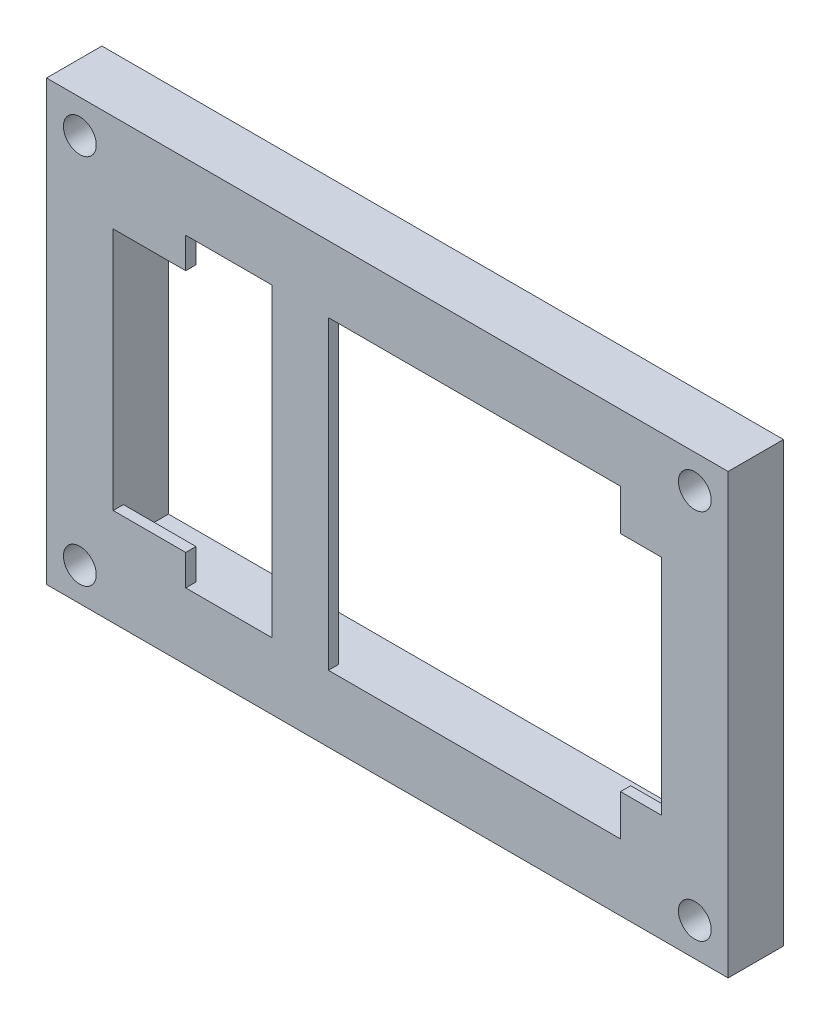
SolidWorks part; units mm, degrees
ref_plane "Front" through (0, 0, 0) normal (0, 0, 1) x (1, 0, 0)
ref_plane "Top" through (0, 0, 0) normal (0, 1, 0) x (1, 0, 0)
ref_plane "Right" through (0, 0, 0) normal (1, 0, 0) x (0, 0, -1)
sketch "Szkic1" plane through (0, 0, 0) normal (0, 0, 1) x (1, 0, 0)
  line L1 (-102.3488, 61.0183) -> (-35.8488, 61.0183)
  line L2 (-102.3488, 61.0183) -> (-102.3488, 18.2183)
  line L3 (-102.3488, 18.2183) -> (-35.8488, 18.2183)
  line L4 (-35.8488, 61.0183) -> (-35.8488, 18.2183)
  dimension "D1" = 66.5
  dimension "D2" = 42.8
extrude "Dodanie-wyciągnięcie1" add sketch "Szkic1" along normal blind 5.4
sketch "Szkic2" plane through (0, 0, 5.4) normal (0, 0, 1) x (1, 0, 0)
  line L0 (-35.8488, 18.2183) -> (-35.8488, 61.0183) construction
  line L1 (-42.3488, 54.5183) -> (-95.8488, 54.5183)
  line L2 (-42.3488, 54.5183) -> (-42.3488, 24.7183)
  line L3 (-42.3488, 24.7183) -> (-95.8488, 24.7183)
  line L4 (-95.8488, 54.5183) -> (-95.8488, 24.7183)
  line L5 (-35.8488, 61.0183) -> (-102.3488, 61.0183) construction
  line L6 (-102.3488, 18.2183) -> (-35.8488, 18.2183) construction
  line L7 (-102.3488, 61.0183) -> (-102.3488, 18.2183) construction
  dimension "D1" = 6.5
  dimension "D2" = 6.5
  dimension "D3" = 6.5
  dimension "D4" = 6.5
extrude "Wytnij-wyciągnięcie1" cut sketch "Szkic2" against normal through all
sketch "Szkic3" plane through (0, 0, 5.4) normal (0, 0, 1) x (1, 0, 0)
  line L0 (-42.3488, 54.5183) -> (-35.8488, 61.0183) construction
  line L1 (-42.3488, 24.7183) -> (-35.8488, 18.2183) construction
  line L2 (-95.8488, 24.7183) -> (-102.3488, 18.2183) construction
  line L3 (-95.8488, 54.5183) -> (-102.3488, 61.0183) construction
  circle A1 centre (-99.0988, 57.7683) radius 1.6
  circle A2 centre (-39.0988, 57.7683) radius 1.6
  circle A3 centre (-39.0988, 21.4683) radius 1.6
  circle A4 centre (-99.0988, 21.4683) radius 1.6
extrude "Wytnij-wyciągnięcie2" cut sketch "Szkic3" against normal blind 10
sketch "Szkic5" plane through (0, 54.5183, 0) normal (0, -1, 0) x (1, 0, 0)
  line L0 (-80.3488, 5.4) -> (-80.3488, 4.4)
  line L1 (-42.3488, 5.4) -> (-95.8488, 5.4) construction
  line L2 (-80.3488, 4.4) -> (-74.8488, 4.4)
  line L3 (-74.8488, 4.4) -> (-74.8488, 5.4)
  line L4 (-74.8488, 5.4) -> (-80.3488, 5.4)
  dimension "D1" = 15.5
  dimension "D2" = 21
  dimension "D3" = 1
extrude "Dodanie-wyciągnięcie2" add sketch "Szkic5" along normal up to surface (29.8 mm away) up to face at (-69.0988, 24.7183, 2.7)
sketch "Szkic6" plane through (0, 54.5183, 0) normal (0, -1, 0) x (1, 0, 0)
  line L1 (-42.3488, 5.4) -> (-46.3488, 5.4)
  line L2 (-42.3488, 5.4) -> (-42.3488, 4.4)
  line L3 (-42.3488, 4.4) -> (-46.3488, 4.4)
  line L4 (-46.3488, 5.4) -> (-46.3488, 4.4)
  dimension "D1" = 4
  dimension "D2" = 1
extrude "Dodanie-wyciągnięcie3" add sketch "Szkic6" along normal blind 4
sketch "Szkic7" plane through (0, 24.7183, 0) normal (0, 1, 0) x (1, 0, 0)
  line L1 (-42.3488, -5.4) -> (-46.3488, -5.4)
  line L2 (-42.3488, -5.4) -> (-42.3488, -4.4)
  line L3 (-42.3488, -4.4) -> (-46.3488, -4.4)
  line L4 (-46.3488, -5.4) -> (-46.3488, -4.4)
  dimension "D1" = 4
  dimension "D2" = 1
extrude "Dodanie-wyciągnięcie4" add sketch "Szkic7" along normal blind 4
sketch "Szkic8" plane through (0, 54.5183, 0) normal (0, -1, 0) x (1, 0, 0)
  line L1 (-95.8488, 5.4) -> (-88.7687, 5.4)
  line L2 (-95.8488, 5.4) -> (-95.8488, 4.4)
  line L3 (-95.8488, 4.4) -> (-88.7687, 4.4)
  line L4 (-88.7687, 5.4) -> (-88.7687, 4.4)
  dimension "D1" = 1
extrude "Dodanie-wyciągnięcie5" add sketch "Szkic8" along normal blind 3
sketch "Szkic9" plane through (0, 24.7183, 0) normal (0, 1, 0) x (1, 0, 0)
  line L1 (-95.8488, -5.4) -> (-88.7688, -5.4)
  line L2 (-95.8488, -5.4) -> (-95.8488, -4.4)
  line L3 (-95.8488, -4.4) -> (-88.7688, -4.4)
  line L4 (-88.7688, -5.4) -> (-88.7688, -4.4)
  dimension "D1" = 1
  dimension "D2" = 7.08
extrude "Dodanie-wyciągnięcie6" add sketch "Szkic9" along normal blind 3
